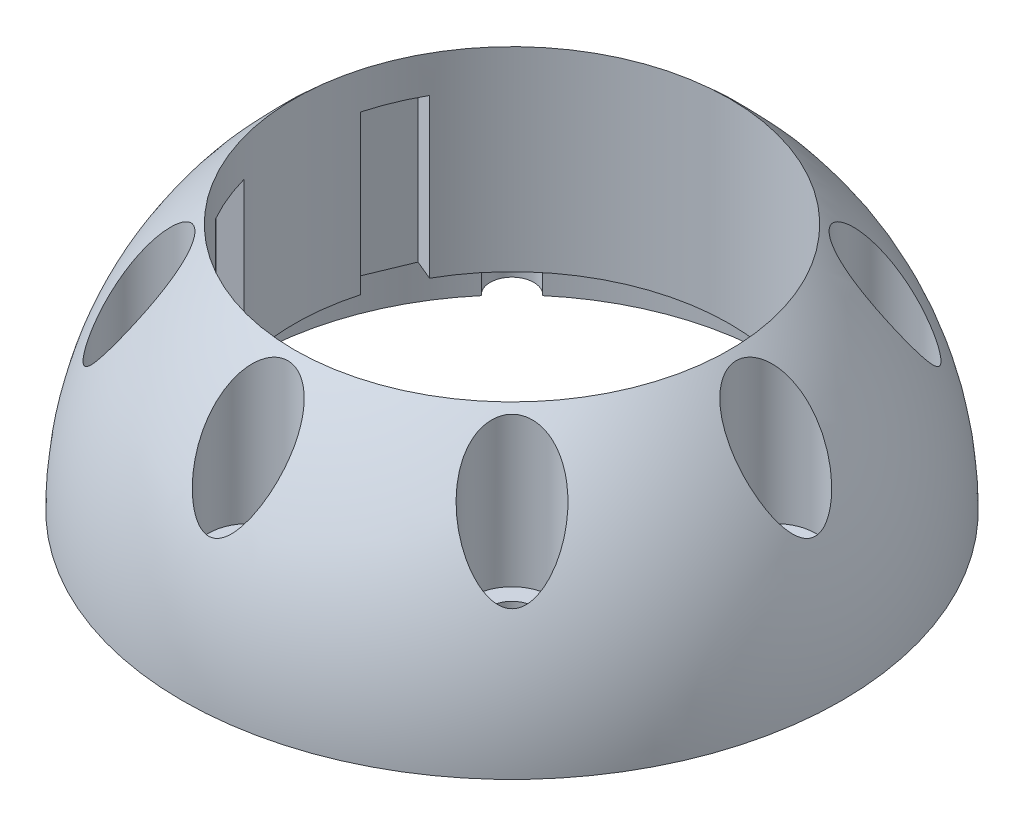
SolidWorks part; units mm, degrees
ref_plane "Front Plane" through (0, 0, 0) normal (0, 0, 1) x (1, 0, 0)
ref_plane "Top Plane" through (0, 0, 0) normal (0, 1, 0) x (1, 0, 0)
ref_plane "Right Plane" through (0, 0, 0) normal (1, 0, 0) x (0, 0, -1)
sketch "Sketch1" plane through (0, 0, 0) normal (0, 1, 0) x (1, 0, 0)
  line L0 (-25, 0) -> (25, 0)
  arc A0 (25, 0) -> (-25, 0) centre (0, 0) ccw
  dimension "D1" = 50
revolve "Revolve1" add sketch "Sketch1" angle 180 about L0
sketch "Sketch2" plane through (0, 0, 0) normal (0, -1, 0) x (1, 0, 0)
  circle A0 centre (20, 0) radius 3
  circle A1 centre (14.1421, -14.1421) radius 3
  circle A2 centre (0, -20) radius 3
  circle A3 centre (-14.1421, -14.1421) radius 3
  circle A4 centre (-20, 0) radius 3
  circle A5 centre (-14.1421, 14.1421) radius 3
  circle A6 centre (0, 20) radius 3
  circle A7 centre (14.1421, 14.1421) radius 3
  dimension "D1" = 6
  dimension "D2" = 20
  dimension "D3" = 8
extrude "Cut-Extrude2" cut sketch "Sketch2" against normal blind 27
sketch "Sketch3" plane through (0, 0, 0) normal (0, -1, 0) x (-1, 0, 0)
  circle A0 centre (-20, 0) radius 3
  circle A1 centre (-20, 0) radius 1.5
  circle A2 centre (-14.1421, 14.1421) radius 1.5
  circle A3 centre (-14.1421, 14.1421) radius 3
  circle A4 centre (0, 20) radius 1.5
  circle A5 centre (0, 20) radius 3
  circle A6 centre (14.1421, 14.1421) radius 1.5
  circle A7 centre (14.1421, 14.1421) radius 3
  circle A8 centre (20, 0) radius 1.5
  circle A9 centre (20, 0) radius 3
  circle A10 centre (14.1421, -14.1421) radius 1.5
  circle A11 centre (14.1421, -14.1421) radius 3
  circle A12 centre (0, -20) radius 1.5
  circle A13 centre (0, -20) radius 3
  circle A14 centre (-14.1421, -14.1421) radius 1.5
  circle A15 centre (-14.1421, -14.1421) radius 3
  dimension "D1" = 3
  dimension "D2" = 8
extrude "Boss-Extrude1" add sketch "Sketch3" against normal blind 7
sketch "Sketch4" plane through (0, 0, 0) normal (0, -1, 0) x (1, 0, 0)
  circle A0 centre (0, 0) radius 20
extrude "Cut-Extrude3" cut sketch "Sketch4" against normal blind 4
sketch "Sketch5" plane through (0, 4, 0) normal (0, -1, 0) x (-1, 0, 0)
  circle A0 centre (0, 0) radius 16.5
  dimension "D1" = 33
extrude "Cut-Extrude4" cut sketch "Sketch5" against normal blind 22
sketch "Sketch6" plane through (0, 4, 0) normal (0, -1, 0) x (1, 0, 0)
  line L0 (0, 0) -> (0, -16.5) construction
  line L1 (0, -16.5) -> (0, -20) construction
  line L2 (0, 0) -> (-18.4776, -7.6537) construction
  line L3 (-17.3952, -5.0405) -> (-15.8645, -8.7361)
  line L4 (-15.8645, -8.7361) -> (-12.3871, -7.2957)
  line L5 (-12.3871, -7.2957) -> (-13.9178, -3.6002)
  line L6 (-17.3952, -5.0405) -> (-13.9178, -3.6002)
  line L7 (0, 0) -> (-20, 0) construction
  line L8 (-17.3952, 5.0405) -> (-13.9178, 3.6002)
  line L9 (-12.3871, 7.2957) -> (-13.9178, 3.6002)
  line L10 (-15.8645, 8.7361) -> (-12.3871, 7.2957)
  line L11 (-17.3952, 5.0405) -> (-15.8645, 8.7361)
  line L12 (17.3952, 5.0405) -> (15.8645, 8.7361)
  line L13 (15.8645, 8.7361) -> (12.3871, 7.2957)
  line L14 (12.3871, 7.2957) -> (13.9178, 3.6002)
  line L15 (17.3952, 5.0405) -> (13.9178, 3.6002)
  line L16 (17.3952, -5.0405) -> (13.9178, -3.6002)
  line L17 (12.3871, -7.2957) -> (13.9178, -3.6002)
  line L18 (15.8645, -8.7361) -> (12.3871, -7.2957)
  line L19 (17.3952, -5.0405) -> (15.8645, -8.7361)
  circle A0 centre (0, 0) radius 16.5 construction
  arc A1 (-19.9437, -1.4989) -> (-15.1623, -13.0424) centre (0, 0) ccw construction
  point P17 (-13.1524, -5.4479)
  point P18 (-16.6298, -6.8883)
  point P24 (-16.6298, 6.8883)
  point P25 (-13.1524, 5.4479)
  point P30 (13.1524, 5.4479)
  point P31 (16.6298, 6.8883)
  point P36 (16.6298, -6.8883)
  point P37 (13.1524, -5.4479)
  dimension "D1" = 18
  dimension "D2" = 2
extrude "Cut-Extrude5" cut sketch "Sketch6" against normal blind 12
sketch "Sketch7" plane through (0, 4, 0) normal (0, -1, 0) x (1, 0, 0)
  circle A0 centre (14.1421, 14.1421) radius 1.65
  circle A1 centre (20, 0) radius 1.65
  circle A2 centre (14.1421, -14.1421) radius 1.65
  circle A3 centre (0, -20) radius 1.65
  circle A4 centre (-14.1421, -14.1421) radius 1.65
  circle A5 centre (-20, 0) radius 1.65
  circle A6 centre (-14.1421, 14.1421) radius 1.65
  circle A7 centre (0, 20) radius 1.65
  dimension "D1" = 3.3
  dimension "D2" = 8
extrude "Cut-Extrude6" cut sketch "Sketch7" against normal mid plane 20
